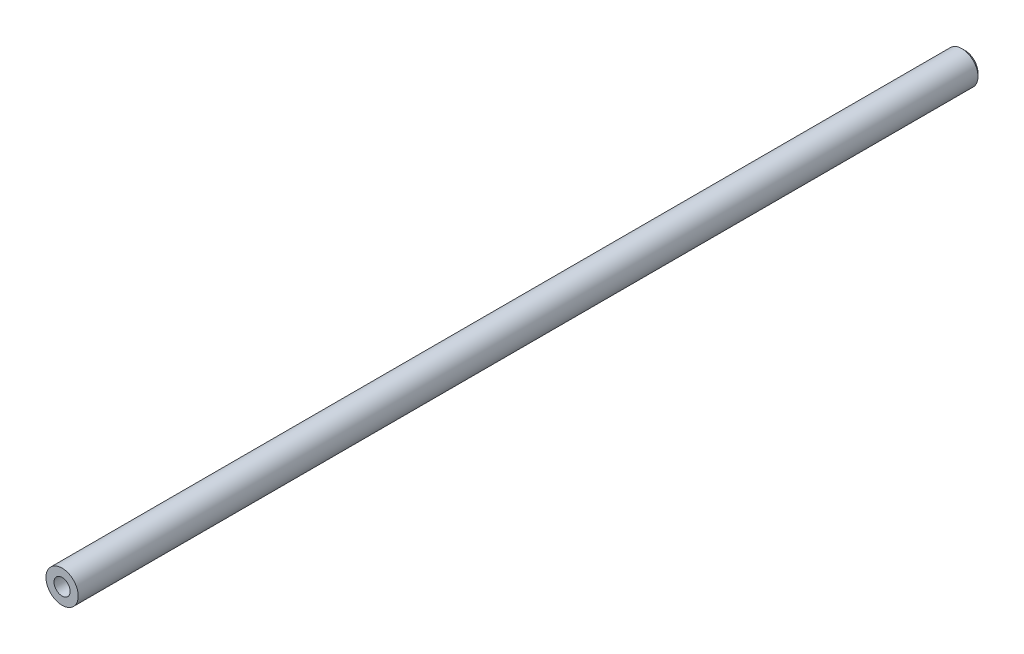
SolidWorks part; units mm, degrees
ref_plane "Alzado" through (0, 0, 0) normal (0, 0, 1) x (1, 0, 0)
ref_plane "Planta" through (0, 0, 0) normal (0, 1, 0) x (1, 0, 0)
ref_plane "Vista lateral" through (0, 0, 0) normal (1, 0, 0) x (0, 0, -1)
sketch "Croquis1" plane through (0, 0, 0) normal (0, 0, 1) x (1, 0, 0)
  circle A0 centre (0, 0) radius 5
  dimension "D1" = 10
extrude "Saliente-Extruir1" add sketch "Croquis1" along normal mid plane 280
hole_wizard "Taladro roscado M61" positions "Croquis3" profile "Croquis2" tap size "M6" standard "Is"
sketch "Croquis3" plane through (0, 0, 140) normal (0, 0, 1) x (1, 0, 0)
  point P0 (0, 0)
sketch "Croquis2" plane through (0, 0, 140) normal (1, 0, 0) x (0, -1, 0)
  line L0 (0, 0) -> (0, 18.5022)
  line L1 (0, 18.5022) -> (2.5, 17)
  line L2 (2.5, 17) -> (2.5, 0)
  line L5 (2.5, 0) -> (0, 0)
  line L10 (0, 18.5022) -> (-2.5, 17) construction
  line L11 (0, -6.35) -> (0, 107.95) construction
  dimension "Diámetro de perforador para roscar" = 5
  dimension "Profundidad de perforador para roscar" = 17
  dimension "Ángulo de perforador" = 118
cosmetic thread "Rosca de taladro1"
hole_wizard "Taladro roscado M62" positions "Croquis5" profile "Croquis4" tap size "M6" standard "Is"
sketch "Croquis5" plane through (0, 0, -140) normal (0, 0, -1) x (-1, 0, 0)
  point P0 (0, 0)
sketch "Croquis4" plane through (0, 0, -140) normal (1, 0, 0) x (0, 1, 0)
  line L0 (0, 0) -> (0, 18.5022)
  line L1 (0, 18.5022) -> (2.5, 17)
  line L2 (2.5, 17) -> (2.5, 0)
  line L5 (2.5, 0) -> (0, 0)
  line L10 (0, 18.5022) -> (-2.5, 17) construction
  line L11 (0, -6.35) -> (0, 107.95) construction
  dimension "Diámetro de perforador para roscar" = 5
  dimension "Profundidad de perforador para roscar" = 17
  dimension "Ángulo de perforador" = 118
cosmetic thread "Rosca de taladro2"
chamfer "Chaflán1" distance 1 angle 45 1 edges at (5, 0, -140)
